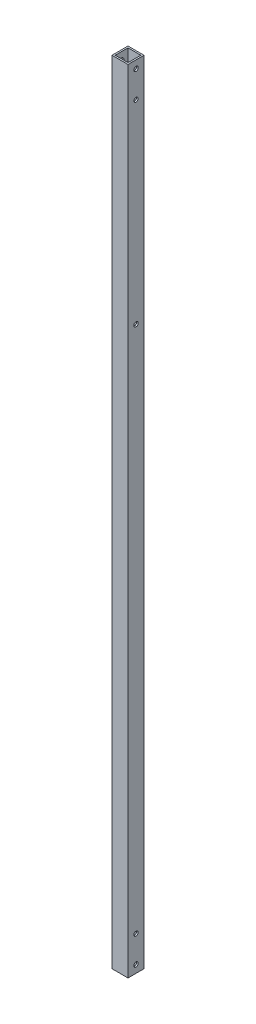
SolidWorks part; units mm, degrees
material "1060 合金"
ref_plane "正面" through (0, 0, 0) normal (0, 0, 1) x (1, 0, 0)
ref_plane "平面" through (0, 0, 0) normal (0, 1, 0) x (1, 0, 0)
ref_plane "右側面" through (0, 0, 0) normal (1, 0, 0) x (0, 0, -1)
sketch "ｽｹｯﾁ1" plane through (0, 0, 0) normal (0, 1, 0) x (1, 0, 0)
  line L1 (-7.5, -7.5) -> (7.5, -7.5)
  line L2 (-7.5, -7.5) -> (-7.5, 7.5)
  line L3 (-7.5, 7.5) -> (7.5, 7.5)
  line L4 (7.5, -7.5) -> (7.5, 7.5)
  line L5 (-7.5, -7.5) -> (7.5, 7.5) construction
  line L6 (-7.5, 7.5) -> (7.5, -7.5) construction
  point P0 (0, 0)
  dimension "D1" = 15
extrude "押し出し-薄板1" add sketch "ｽｹｯﾁ1" along normal blind 741 thin thin type one direction reverse wall 1.5
sketch "ｽｹｯﾁ2" plane through (7.5, 0, 0) normal (1, 0, 0) x (0, 0, -1)
  line L0 (0, 0) -> (0, -50000) construction
  line L2 (-7.5, 370.5) -> (7.5, 370.5) construction
  line L3 (-7.5, 741) -> (-7.5, 0) construction
  line L4 (7.5, 741) -> (7.5, 0) construction
  circle A0 centre (0, 7.29) radius 2.1
  circle A1 centre (0, 32.29) radius 2
  circle A2 centre (0, 708.71) radius 2
  circle A3 centre (0, 733.71) radius 2.1
  circle A4 centre (0, 526.49) radius 2.1
  dimension "D3" = 4.2
  dimension "D4" = 4
  dimension "D6" = 4.2
  dimension "D1" = 25
  dimension "D2" = 726.42
  dimension "D5" = 207.22
extrude "ｶｯﾄ - 押し出し1" cut sketch "ｽｹｯﾁ2" against normal through all
equation "\"D2@ｽｹｯﾁ2\"=sqr( 675^2+268.45^2 )"
